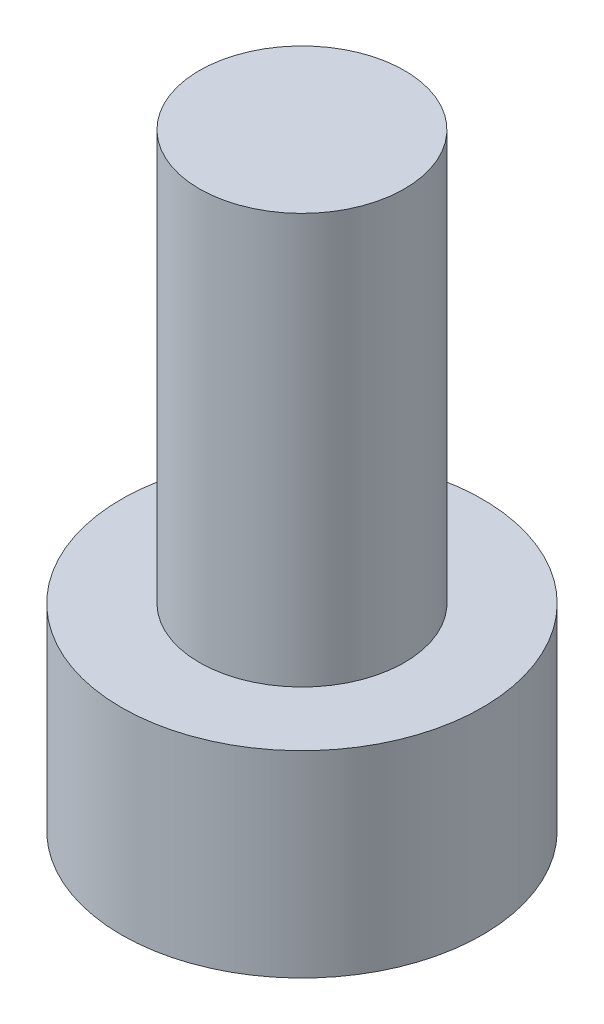
SolidWorks part; units mm, degrees
material "AISI 304"
ref_plane "前视基准面" through (0, 0, 0) normal (0, 0, 1) x (1, 0, 0)
ref_plane "上视基准面" through (0, 0, 0) normal (0, 1, 0) x (1, 0, 0)
ref_plane "右视基准面" through (0, 0, 0) normal (1, 0, 0) x (0, 0, -1)
other "Configuration Table"
sketch "草图1" plane through (0, 0, 0) normal (0, 1, 0) x (1, 0, 0)
  circle A0 centre (0, 0) radius 2.2
  dimension "D1" = 4.4
extrude "凸台-拉伸1" add sketch "草图1" along normal blind 2.4
sketch "草图2" plane through (0, 2.4, 0) normal (0, 1, 0) x (1, 0, 0)
  circle A0 centre (0, 0) radius 1.25
  dimension "D1" = 2.5
extrude "凸台-拉伸2" add sketch "草图2" along normal blind 5
sketch "草图3" plane through (0, 0, 0) normal (0, -1, 0) x (1, 0, 0)
  line L1 (0.5764, 1.0005) -> (-0.5783, 0.9995)
  line L2 (-0.5783, 0.9995) -> (-1.1547, -0.0011)
  line L3 (-1.1547, -0.0011) -> (-0.5764, -1.0005)
  line L4 (-0.5764, -1.0005) -> (0.5783, -0.9995)
  line L5 (0.5783, -0.9995) -> (1.1547, 0.0011)
  line L6 (1.1547, 0.0011) -> (0.5764, 1.0005)
  circle A0 centre (0, 0) radius 1 construction
  dimension "D1" = 2
extrude "切除-拉伸1" cut sketch "草图3" against normal blind 1
